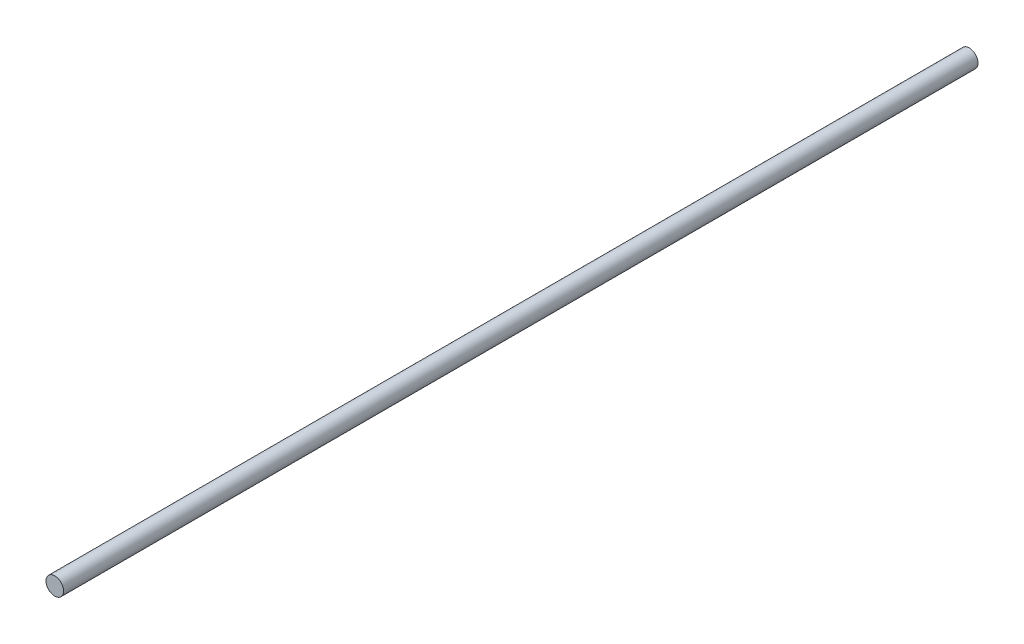
SolidWorks part; units mm, degrees
material "1.4000 (X6Cr13)"
ref_plane "Plan de face" through (0, 0, 0) normal (0, 0, 1) x (1, 0, 0)
ref_plane "Plan de dessus" through (0, 0, 0) normal (0, 1, 0) x (1, 0, 0)
ref_plane "Plan de droite" through (0, 0, 0) normal (1, 0, 0) x (0, 0, -1)
sketch "Esquisse1" plane through (0, 0, 0) normal (0, 0, 1) x (1, 0, 0)
  circle A0 centre (0, 0) radius 4
extrude "Boss.-Extru.1" add sketch "Esquisse1" along normal blind 416
ref_plane "SectionMiBarreY" through (0, 0, 208) normal (0, 0, -1) x (-1, 0, 0)
